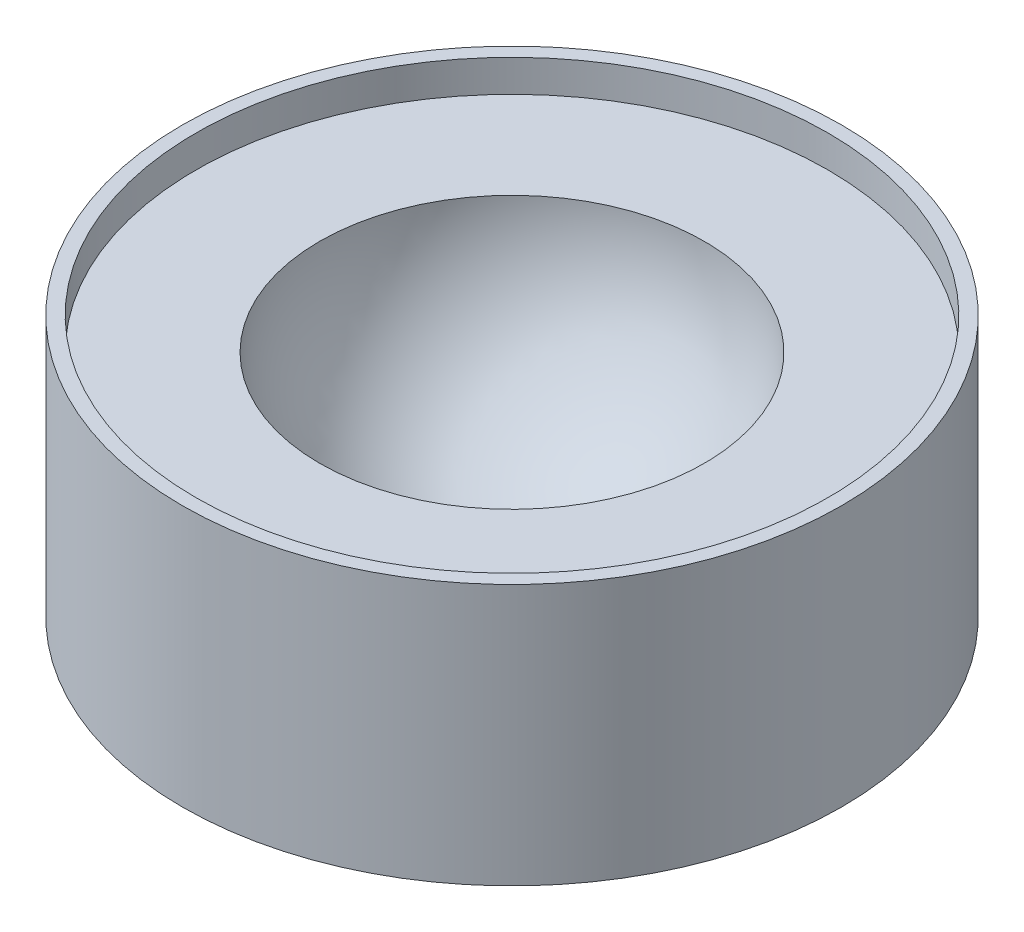
SolidWorks part; units mm, degrees
ref_plane "Front Plane" through (0, 0, 0) normal (0, 0, 1) x (1, 0, 0)
ref_plane "Top Plane" through (0, 0, 0) normal (0, 1, 0) x (1, 0, 0)
ref_plane "Right Plane" through (0, 0, 0) normal (1, 0, 0) x (0, 0, -1)
sketch "Sketch1" plane through (0, 0, 0) normal (0, 1, 0) x (1, 0, 0)
  circle A0 centre (0, 0) radius 72
  dimension "D1" = 144
extrude "Boss-Extrude4" add sketch "Sketch1" along normal blind 50
sketch "Sketch4" plane through (0, 0, 0) normal (0, 0, 1) x (1, 0, 0)
  line L0 (72, 50) -> (-72, 50) construction
  line L1 (0, 50) -> (42, 50)
  line L2 (0, 50) -> (0, 8)
  arc A0 (0, 8) -> (42, 50) centre (0, 50) ccw
  dimension "D1" = 84
revolve "Cut-Revolve2" cut sketch "Sketch4" angle 360 about L2
sketch "Sketch5" plane through (0, 50, 0) normal (0, 1, 0) x (1, 0, 0)
  circle A0 centre (0, 0) radius 72
  circle A1 centre (0, 0) radius 69
  dimension "D1" = 138
extrude "Boss-Extrude5" add sketch "Sketch5" along normal blind 7
